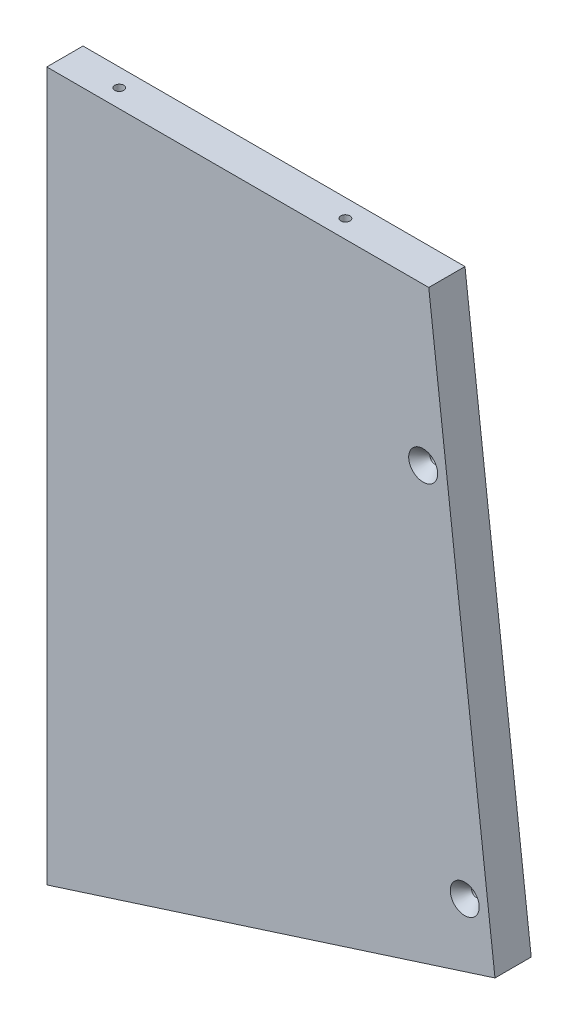
SolidWorks part; units mm, degrees
material "Beech"
ref_plane "Front Plane" through (0, 0, 0) normal (0, 0, 1) x (1, 0, 0)
ref_plane "Top Plane" through (0, 0, 0) normal (0, 1, 0) x (1, 0, 0)
ref_plane "Right Plane" through (0, 0, 0) normal (1, 0, 0) x (0, 0, -1)
sketch "Sketch1" plane through (0, 0, 0) normal (0, 0, 1) x (1, 0, 0)
  line L1 (-222.053, -248.25) -> (-222.053, 0) construction
  line L2 (-88.1902, 0) -> (-222.053, 0)
  line L3 (-222.053, -248.25) -> (-222.053, 0)
  line L4 (-91.9973, 0) -> (-234.753, 0) construction
  line L7 (-64.9774, -197.966) -> (-88.1902, 0)
  line L8 (-64.9774, -197.966) -> (-222.053, -248.25)
extrude "Boss-Extrude1" add sketch "Sketch1" against normal blind 12.7
hole_wizard "Hole1" positions "Sketch2" profile "Sketch3" legacy
sketch "Sketch2" plane through (181.0394, 12.7, 123.1167) normal (0, 1, 0) x (0, 0, -1)
  line L0 (-129.4667, 415.7924) -> (-129.4667, 273.0368) construction
  line L5 (-135.8167, 409.4424) -> (135.5488, 409.4424) construction
  line L10 (-135.8167, 279.3868) -> (135.5488, 279.3868) construction
  line L11 (-0.134, 409.4424) -> (-0.134, 279.3868) construction
  point P22 (-129.4667, 384.0424)
  point P24 (-129.4667, 304.7868)
  point P26 (-110.4167, 409.4424)
  point P30 (-0.134, 409.4424)
  point P50 (110.1488, 409.4424)
  point P51 (129.1988, 304.7868)
  point P52 (129.1988, 384.0424)
sketch "Sketch3" plane through (-203.003, 12.7, -6.082) normal (1, 0, 0) x (0, 0, 1)
  line L0 (0, 0) -> (0, 32.7039)
  line L1 (0, 32.7039) -> (1.5875, 31.75)
  line L2 (1.5875, 31.75) -> (1.5875, 4.0177)
  line L3 (1.5875, 4.0177) -> (5.08, 0)
  line L4 (5.08, 0) -> (0, 0)
  line L5 (0, -14.3089) -> (0, 102.4216) construction
  line L6 (0, 32.7039) -> (-1.5875, 31.75) construction
  line L7 (-1.5875, 4.0177) -> (-5.08, 0) construction
  dimension "Diameter" = 3.175
  dimension "Depth" = 31.75
  dimension "C-Sink Diameter" = 10.16
  dimension "C-Sink Angle" = 82
  dimension "Drill Angle" = 118
hole_wizard "Hole3" positions "Sketch6" profile "Sketch7" legacy
sketch "Sketch6" plane through (-234.753, 1073.3642, -135.8167) normal (-1, 0, 0) x (0, 0, -1)
  line L3 (-0.134, 1338.7628) -> (-0.134, 1090.5128) construction
  point P1 (-129.4667, 1300.6628)
  point P3 (-129.4667, 1128.6128)
  point P15 (129.1988, 1128.6128)
  point P16 (129.1988, 1300.6628)
sketch "Sketch7" plane through (-234.753, -227.2986, -6.35) normal (0, 1, 0) x (0, 0, 1)
  line L0 (0, 0) -> (0, 32.7039)
  line L1 (0, 32.7039) -> (1.5875, 31.75)
  line L2 (1.5875, 31.75) -> (1.5875, 4.0177)
  line L3 (1.5875, 4.0177) -> (5.08, 0)
  line L4 (5.08, 0) -> (0, 0)
  line L5 (0, -14.3089) -> (0, 102.4216) construction
  line L6 (0, 32.7039) -> (-1.5875, 31.75) construction
  line L7 (-1.5875, 4.0177) -> (-5.08, 0) construction
  dimension "Diameter" = 3.175
  dimension "Depth" = 31.75
  dimension "C-Sink Diameter" = 10.16
  dimension "C-Sink Angle" = 82
  dimension "Drill Angle" = 118
hole_wizard "Hole5" positions "Sketch10" profile "Sketch11" legacy
sketch "Sketch10" plane through (-234.753, 1090.5128, 123.1167) normal (-1, 0, 0) x (0, 0, -1)
  line L3 (-0.134, 1338.7628) -> (-0.134, 1090.5128) construction
  point P1 (-129.4667, 1300.6628)
  point P3 (-129.4667, 1128.6128)
  point P15 (129.1988, 1128.6128)
  point P16 (129.1988, 1300.6628)
sketch "Sketch11" plane through (-234.753, -210.15, 252.5835) normal (0, 1, 0) x (0, 0, 1)
  line L0 (0, 0) -> (0, 32.7039)
  line L1 (0, 32.7039) -> (1.5875, 31.75)
  line L2 (1.5875, 31.75) -> (1.5875, 4.0177)
  line L3 (1.5875, 4.0177) -> (5.08, 0)
  line L4 (5.08, 0) -> (0, 0)
  line L5 (0, -14.3089) -> (0, 102.4216) construction
  line L6 (0, 32.7039) -> (-1.5875, 31.75) construction
  line L7 (-1.5875, 4.0177) -> (-5.08, 0) construction
  dimension "Diameter" = 3.175
  dimension "Depth" = 31.75
  dimension "C-Sink Diameter" = 10.16
  dimension "C-Sink Angle" = 82
  dimension "Drill Angle" = 118
hole_wizard "Hole6" positions "Sketch12" profile "Sketch13" legacy
sketch "Sketch12" plane through (181.0394, 1073.3642, 0) normal (0, 0, 1) x (-0.9272, -0.3746, 0)
  point P29 (707.1666, 1065.2704)
  point P31 (674.128, 944.6031)
sketch "Sketch13" plane through (-75.5767, -179.2465, 0) normal (1, 0, 0) x (0, -1, 0)
  line L0 (0, 0) -> (0, 39.0539)
  line L1 (0, 39.0539) -> (1.5875, 38.1)
  line L2 (1.5875, 38.1) -> (1.5875, 4.0177)
  line L3 (1.5875, 4.0177) -> (5.08, 0)
  line L4 (5.08, 0) -> (0, 0)
  line L5 (0, -14.3089) -> (0, 102.4216) construction
  line L6 (0, 39.0539) -> (-1.5875, 38.1) construction
  line L7 (-1.5875, 4.0177) -> (-5.08, 0) construction
  dimension "Diameter" = 3.175
  dimension "Depth" = 38.1
  dimension "C-Sink Diameter" = 10.16
  dimension "C-Sink Angle" = 82
  dimension "Drill Angle" = 118
hole_wizard "Hole7" positions "Sketch14" profile "Sketch15" legacy
sketch "Sketch14" plane through (181.0394, 12.7, -135.8167) normal (0, 1, 0) x (0, 0, -1)
  line L0 (-129.4667, 415.7924) -> (-129.4667, 273.0368) construction
  line L5 (-135.8167, 409.4424) -> (135.5488, 409.4424) construction
  line L10 (-135.8167, 279.3868) -> (135.5488, 279.3868) construction
  line L11 (-0.134, 409.4424) -> (-0.134, 279.3868) construction
  point P22 (-129.4667, 384.0424)
  point P24 (-129.4667, 304.7868)
  point P26 (-110.4167, 409.4424)
  point P30 (-0.134, 409.4424)
  point P50 (110.1488, 409.4424)
  point P51 (129.1988, 304.7868)
  point P52 (129.1988, 384.0424)
sketch "Sketch15" plane through (-203.003, 12.7, -265.0155) normal (1, 0, 0) x (0, 0, 1)
  line L0 (0, 0) -> (0, 32.7039)
  line L1 (0, 32.7039) -> (1.5875, 31.75)
  line L2 (1.5875, 31.75) -> (1.5875, 4.0177)
  line L3 (1.5875, 4.0177) -> (5.08, 0)
  line L4 (5.08, 0) -> (0, 0)
  line L5 (0, -14.3089) -> (0, 102.4216) construction
  line L6 (0, 32.7039) -> (-1.5875, 31.75) construction
  line L7 (-1.5875, 4.0177) -> (-5.08, 0) construction
  dimension "Diameter" = 3.175
  dimension "Depth" = 31.75
  dimension "C-Sink Diameter" = 10.16
  dimension "C-Sink Angle" = 82
  dimension "Drill Angle" = 118
hole_wizard "Hole8" positions "Sketch16" profile "Sketch17" legacy
sketch "Sketch16" plane through (531.1976, -20.4499, -135.8167) normal (0.3049, -0.9524, 0) x (0, 0, 1)
  line L0 (129.4667, 798.9359) -> (129.4667, 624.9146) construction
  line L5 (0.134, 798.9359) -> (0, 625.1618) construction
  point P10 (129.4667, 663.0146)
  point P12 (129.4667, 760.8359)
  point P20 (-129.4082, 663.2142)
  point P21 (-129.2574, 761.0354)
sketch "Sketch17" plane through (-193.6044, -252.4777, -265.0741) normal (0, 0, 1) x (0.9524, 0.3049, 0)
  line L0 (0, 0) -> (0, 32.7039)
  line L1 (0, 32.7039) -> (1.5875, 31.75)
  line L2 (1.5875, 31.75) -> (1.5875, 4.0177)
  line L3 (1.5875, 4.0177) -> (5.08, 0)
  line L4 (5.08, 0) -> (0, 0)
  line L5 (0, -14.3089) -> (0, 102.4216) construction
  line L6 (0, 32.7039) -> (-1.5875, 31.75) construction
  line L7 (-1.5875, 4.0177) -> (-5.08, 0) construction
  dimension "Diameter" = 3.175
  dimension "Depth" = 31.75
  dimension "C-Sink Diameter" = 10.16
  dimension "C-Sink Angle" = 82
  dimension "Drill Angle" = 118
